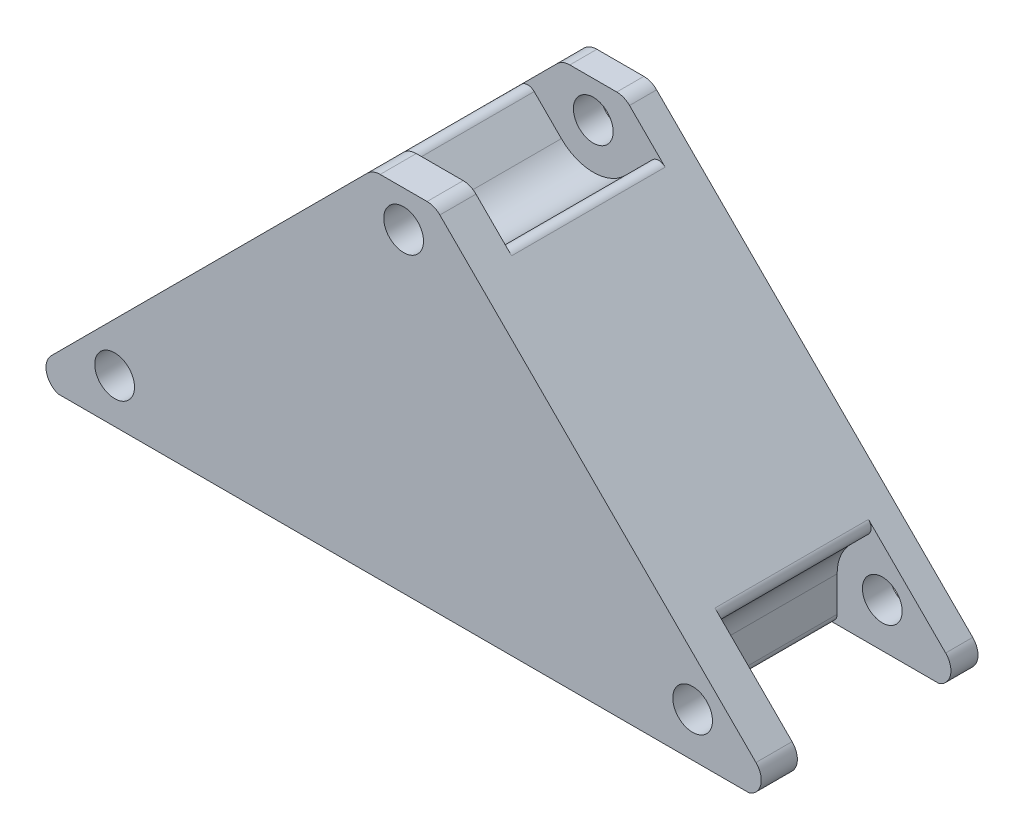
SolidWorks part; units mm, degrees
ref_plane "前视基准面" through (0, 0, 0) normal (0, 0, 1) x (1, 0, 0)
ref_plane "上视基准面" through (0, 0, 0) normal (0, 1, 0) x (1, 0, 0)
ref_plane "右视基准面" through (0, 0, 0) normal (1, 0, 0) x (0, 0, -1)
other "Configuration Table"
sketch "草图1" plane through (0, 0, 0) normal (0, 0, 1) x (1, 0, 0)
  line L0 (-71.0987, -145.8448) -> (5.4619, -145.8448)
  line L4 (-36.2448, -106.9648) -> (-75.2448, -145.9648)
  line L5 (-75.2448, -145.9648) -> (9.608, -145.9648)
  line L6 (9.608, -145.9648) -> (-29.392, -106.9648)
  line L7 (-29.392, -106.9648) -> (-36.2448, -106.9648)
  line L8 (-36.8306, -107.5506) -> (-71.8306, -142.5506)
  line L9 (-70.4164, -145.9648) -> (4.7796, -145.9648)
  line L10 (6.1938, -142.5506) -> (-28.8062, -107.5506)
  line L11 (-30.2204, -106.9648) -> (-35.4164, -106.9648)
  arc A0 (-36.8306, -107.5506) -> (-35.4164, -106.9648) centre (-35.4164, -108.9648) cw
  arc A1 (-28.8062, -107.5506) -> (-30.2204, -106.9648) centre (-30.2204, -108.9648) ccw
  arc A2 (4.7796, -145.9648) -> (6.1938, -142.5506) centre (4.7796, -143.9648) ccw
  arc A3 (-71.8306, -142.5506) -> (-70.4164, -145.9648) centre (-70.4164, -143.9648) ccw
  circle A4 centre (-0.8184, -140.9648) radius 2.2
  circle A5 centre (-32.8184, -110.9648) radius 2.2
  circle A6 centre (-64.8184, -140.9648) radius 2.2
  dimension "D2" = 2
  dimension "D3" = 4.4
  dimension "D4" = 4.4
  dimension "D5" = 4.4
  dimension "D6" = 0.12
  dimension "D1" = 0
extrude "凸台-拉伸1" add sketch "草图1" along normal blind 24 contours L8 A3 L0 A2 L10 A1 L11 A0 A6 A5 A4
sketch "草图2" plane through (0, 0, 24) normal (0, 0, 1) x (1, 0, 0)
  line L0 (-40.0671, -110.7871) -> (-36.3539, -114.5003)
  line L1 (-36.8306, -107.5506) -> (-71.8306, -142.5506) construction
  line L2 (-32.8184, -100.2854) -> (-32.8184, -155.1016) construction
  line L3 (-40.0671, -110.7871) -> (-32.8184, -103.5384)
  line L4 (-25.5697, -110.7871) -> (-32.8184, -103.5384)
  line L5 (-25.5697, -110.7871) -> (-29.2829, -114.5003)
  line L6 (-63.9961, -134.716) -> (-61.2829, -137.4292)
  line L7 (-59.8184, -145.8448) -> (-59.8184, -140.9648)
  line L8 (-71.0987, -145.8448) -> (5.4619, -145.8448) construction
  line L9 (-63.9961, -134.716) -> (-75.1248, -145.8448)
  line L10 (-36.2448, -106.9648) -> (-75.2448, -145.9648) construction
  line L11 (-75.1248, -145.8448) -> (-59.8184, -145.8448)
  line L12 (9.488, -145.8448) -> (-5.8184, -145.8448)
  line L13 (-1.6407, -134.716) -> (9.488, -145.8448)
  line L14 (-5.8184, -145.8448) -> (-5.8184, -140.9648)
  line L15 (-1.6407, -134.716) -> (-4.3539, -137.4292)
  arc A0 (-36.3539, -114.5003) -> (-29.2829, -114.5003) centre (-32.8184, -110.9648) ccw
  arc A2 (-59.8184, -140.9648) -> (-61.2829, -137.4292) centre (-64.8184, -140.9648) ccw
  arc A3 (-5.8184, -140.9648) -> (-4.3539, -137.4292) centre (-0.8184, -140.9648) cw
  dimension "D1" = 10
  dimension "D3" = 10
extrude "切除-拉伸1" cut sketch "草图2" against normal blind 17 from offset 4 offset against normal yes
fillet "圆角1" radius 1 6 edges at (-63.9961, -134.716, 11.5) (-59.8184, -145.8448, 11.5) (-1.6407, -134.716, 11.5) (-5.8184, -145.8448, 11.5) (-25.5697, -110.7871, 11.5) (-40.0671, -110.7871, 11.5)
